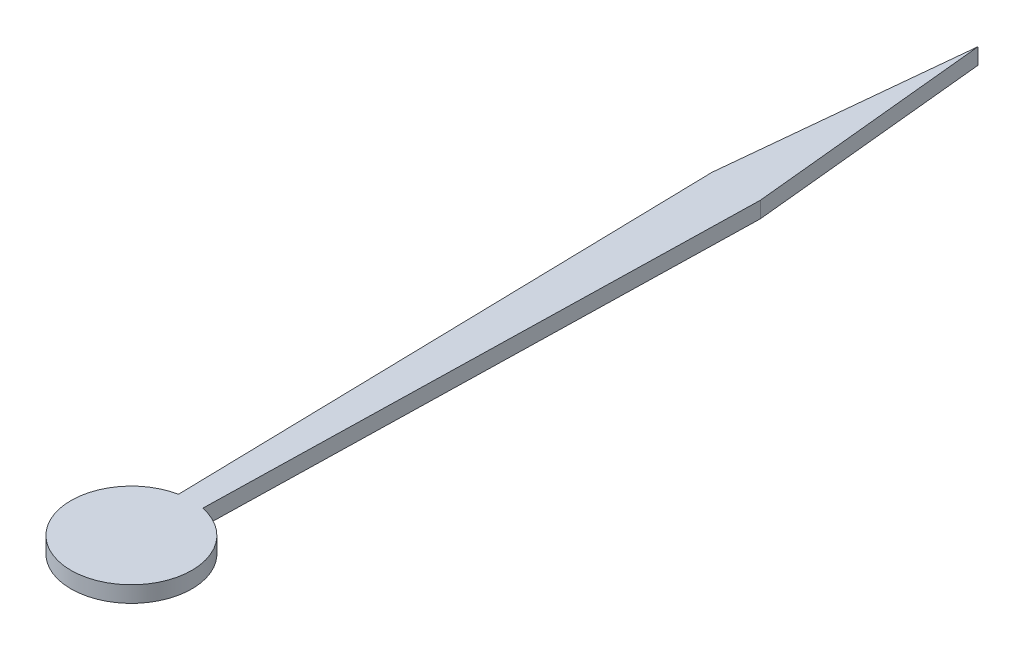
SolidWorks part; units mm, degrees
ref_plane "Front Plane" through (0, 0, 0) normal (0, 0, 1) x (1, 0, 0)
ref_plane "Top Plane" through (0, 0, 0) normal (0, 1, 0) x (1, 0, 0)
ref_plane "Right Plane" through (0, 0, 0) normal (1, 0, 0) x (0, 0, -1)
sketch "Sketch1" plane through (0, 0, 0) normal (0, 1, 0) x (1, 0, 0)
  line L0 (0, 0) -> (0, 10.5) construction
  line L1 (0, 10.5) -> (0.3, 7.5)
  line L2 (-0.3, 7.5) -> (-0.15, 0.7348)
  line L3 (0.3, 7.5) -> (0.15, 0.7348)
  line L4 (0, 10.5) -> (-0.3, 7.5)
  arc A0 (-0.15, 0.7348) -> (0.15, 0.7348) centre (0, 0) ccw
  dimension "D1" = 1.5
  dimension "D2" = 10.5
  dimension "D3" = 0.6
  dimension "D4" = 3
  dimension "D5" = 0.3
extrude "Extrude1" add sketch "Sketch1" along normal blind 0.2
